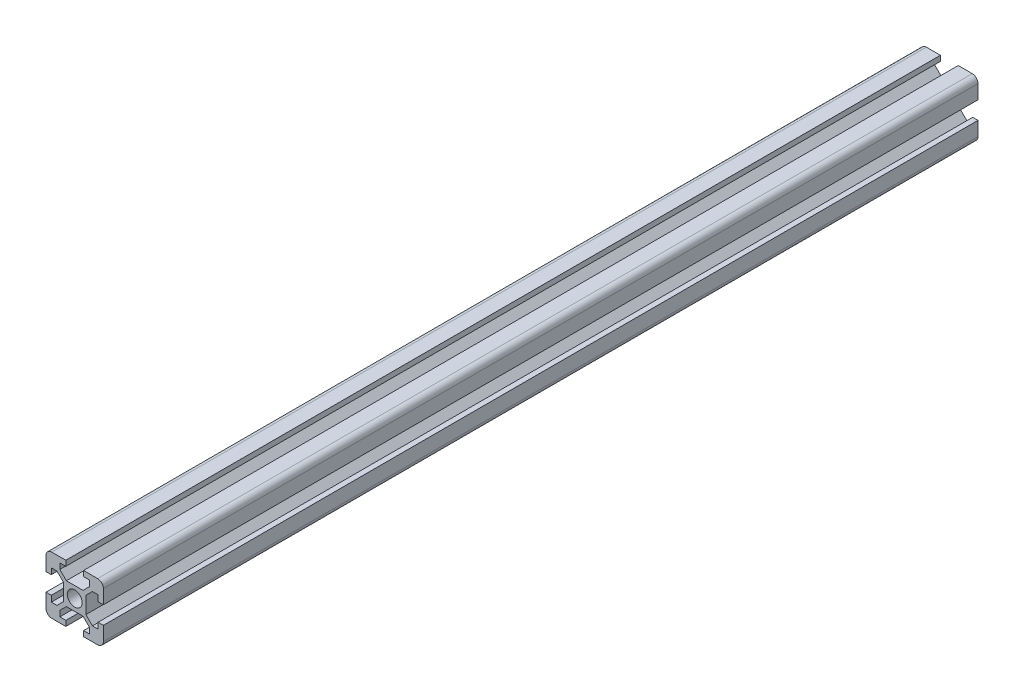
SolidWorks part; units mm, degrees
ref_plane "Front Plane" through (0, 0, 0) normal (0, 0, 1) x (1, 0, 0)
ref_plane "Top Plane" through (0, 0, 0) normal (0, 1, 0) x (1, 0, 0)
ref_plane "Right Plane" through (0, 0, 0) normal (1, 0, 0) x (0, 0, -1)
sketch "Sketch1" plane through (0, 0, 0) normal (0, 0, 1) x (1, 0, 0)
  line L1 (-3.9, 2.9101) -> (-6.1799, 5.19)
  line L2 (-8.15, 5.19) -> (-8.15, 3.1)
  line L3 (-8.15, 3.1) -> (-10, 3.1)
  line L4 (-10, 3.1) -> (-10, 10)
  line L5 (-10, 10) -> (-3.1, 10)
  line L6 (-3.1, 10) -> (-3.1, 8.15)
  line L7 (-3.1, 8.15) -> (-5.19, 8.15)
  line L8 (-5.19, 6.1799) -> (-2.9101, 3.9)
  line L10 (0, 15.4917) -> (0, -11.1126) construction
  line L11 (-16.3459, 0) -> (7.5931, 0) construction
  line L21 (16.3459, 0) -> (-7.5931, 0) construction
  line L39 (-8.15, 5.19) -> (-6.1799, 5.19)
  line L40 (-5.19, 6.1799) -> (-5.19, 8.15)
  line L41 (-3.9, 2.9101) -> (-3.9, -2.9101)
  line L42 (-2.9101, 3.9) -> (2.9101, 3.9)
  line L43 (-2.9101, -3.9) -> (2.9101, -3.9)
  line L44 (-5.19, -6.1799) -> (-5.19, -8.15)
  line L45 (-8.15, -5.19) -> (-6.1799, -5.19)
  line L46 (-5.19, -6.1799) -> (-2.9101, -3.9)
  line L47 (-3.1, -8.15) -> (-5.19, -8.15)
  line L48 (-3.1, -10) -> (-3.1, -8.15)
  line L49 (-10, -10) -> (-3.1, -10)
  line L50 (-10, -3.1) -> (-10, -10)
  line L51 (-8.15, -3.1) -> (-10, -3.1)
  line L52 (-8.15, -5.19) -> (-8.15, -3.1)
  line L53 (-3.9, -2.9101) -> (-6.1799, -5.19)
  line L54 (-16.3459, 0) -> (7.5931, 0) construction
  line L55 (3.9, -2.9101) -> (6.1799, -5.19)
  line L56 (8.15, -5.19) -> (8.15, -3.1)
  line L57 (8.15, -3.1) -> (10, -3.1)
  line L58 (10, -3.1) -> (10, -10)
  line L59 (10, -10) -> (3.1, -10)
  line L60 (3.1, -10) -> (3.1, -8.15)
  line L61 (3.1, -8.15) -> (5.19, -8.15)
  line L62 (5.19, -6.1799) -> (2.9101, -3.9)
  line L63 (8.15, -5.19) -> (6.1799, -5.19)
  line L64 (5.19, -6.1799) -> (5.19, -8.15)
  line L65 (3.9, 2.9101) -> (3.9, -2.9101)
  line L66 (5.19, 6.1799) -> (5.19, 8.15)
  line L67 (8.15, 5.19) -> (6.1799, 5.19)
  line L68 (5.19, 6.1799) -> (2.9101, 3.9)
  line L69 (3.1, 8.15) -> (5.19, 8.15)
  line L70 (3.1, 10) -> (3.1, 8.15)
  line L71 (10, 10) -> (3.1, 10)
  line L72 (10, 3.1) -> (10, 10)
  line L73 (8.15, 3.1) -> (10, 3.1)
  line L74 (8.15, 5.19) -> (8.15, 3.1)
  line L75 (3.9, 2.9101) -> (6.1799, 5.19)
  circle A0 centre (0, 0) radius 2.6
  point P19 (-3.9, 0)
  point P20 (-3.9, 0)
  point P37 (0, -3.9)
  point P38 (0, 3.9)
  point P46 (3.9, 0)
  point P50 (0, -3.9)
  point P53 (0, 3.9)
  dimension "D8" = 5.2
  dimension "D1" = 10
  dimension "D2" = 10
  dimension "D3" = 6.1
  dimension "D4" = 1.4
  dimension "D5" = 6.1
  dimension "D6" = 1.85
  dimension "D7" = 6.9
  dimension "D9" = 4.81
  dimension "D10" = 4.81
extrude "Boss-Extrude1" add sketch "Sketch1" against normal blind 304.8
fillet "Fillet1" radius 2 4 edges at (10, -10, -152.4) (-10, -10, -152.4) (10, 10, -152.4) (-10, 10, -152.4)
